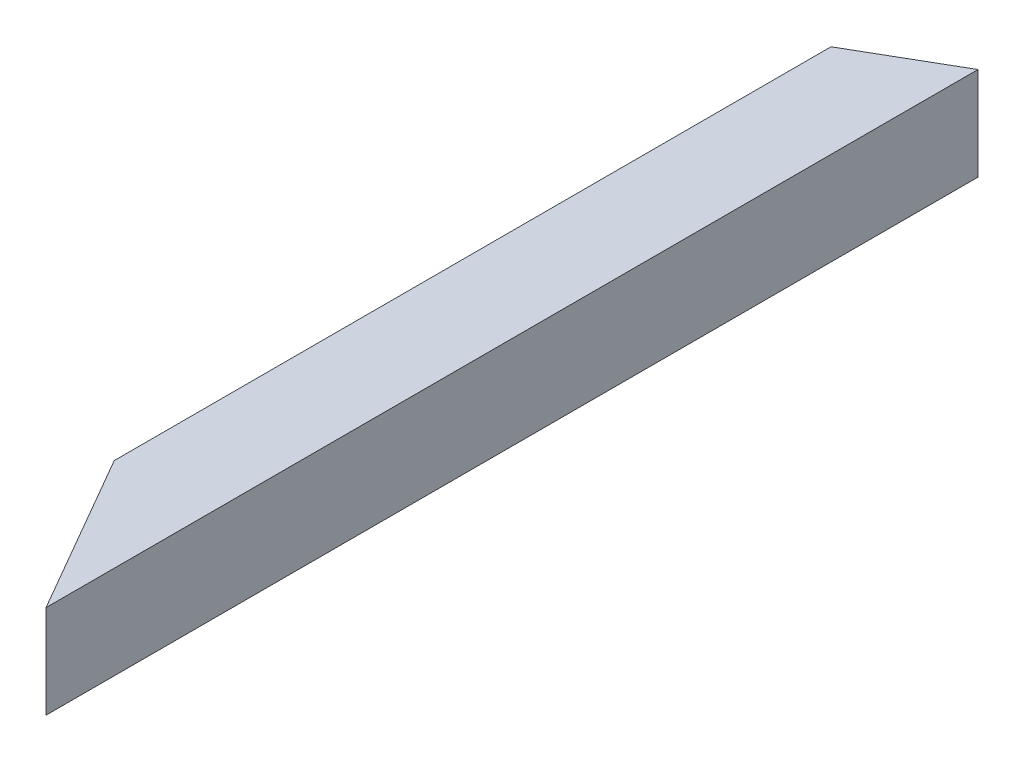
SolidWorks part; units mm, degrees
ref_plane "前视基准面" through (0, 0, 0) normal (0, 0, 1) x (1, 0, 0)
ref_plane "上视基准面" through (0, 0, 0) normal (0, 1, 0) x (1, 0, 0)
ref_plane "右视基准面" through (0, 0, 0) normal (1, 0, 0) x (0, 0, -1)
other "Configuration Table"
sketch "草图1" plane through (0, 0, 0) normal (0, 0, 1) x (1, 0, 0)
  line L1 (0, 0) -> (20, 0)
  line L2 (0, 0) -> (0, 20)
  line L3 (0, 20) -> (20, 20)
  line L4 (20, 0) -> (20, 20)
  line L5 (1, 1) -> (19, 1)
  line L6 (1, 1) -> (1, 19)
  line L7 (1, 19) -> (19, 19)
  line L8 (19, 1) -> (19, 19)
  dimension "D1" = 20
  dimension "D2" = 20
  dimension "D3" = 1
  dimension "D4" = 1
  dimension "D5" = 1
  dimension "D6" = 1
extrude "凸台-拉伸1" add sketch "草图1" along normal blind 200
sketch "草图2" plane through (0, 20, 0) normal (0, 1, 0) x (1, 0, 0)
  line L0 (20, 0) -> (0, -11.547)
  line L1 (0, -200) -> (0, 0) construction
  line L2 (0, -165.359) -> (20, -200)
  line L3 (20, 0) -> (0, 0) construction
  line L4 (0, -11.547) -> (0, 0)
  line L5 (0, 0) -> (20, 0)
  line L6 (0, -165.359) -> (0, -200)
  line L7 (0, -200) -> (20, -200)
  dimension "D1" = 90
  dimension "D2" = 30
extrude "切除-拉伸1" cut sketch "草图2" against normal blind 300
